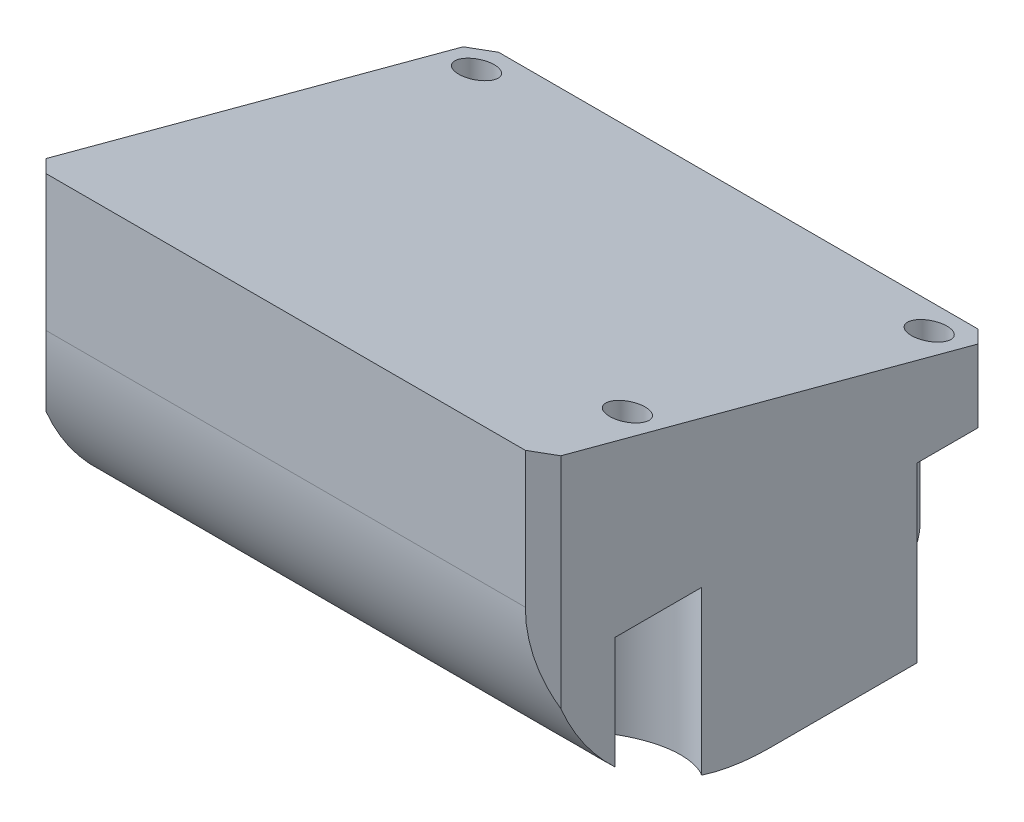
SolidWorks part; units mm, degrees
ref_plane "Front Plane" through (0, 0, 0) normal (0, 0, 1) x (1, 0, 0)
ref_plane "Top Plane" through (0, 0, 0) normal (0, 1, 0) x (1, 0, 0)
ref_plane "Right Plane" through (0, 0, 0) normal (1, 0, 0) x (0, 0, -1)
ref_plane "Plane1" through (-29, 0, 0) normal (-1, 0, 0) x (0, -1, 0)
sketch "Sketch1" plane through (-29, 0, 0) normal (-1, 0, 0) x (0, -1, 0)
  line L0 (125.5, 25.5) -> (84.6933, 25.5)
  line L1 (84.6933, 25.5) -> (98.3587, -25.5)
  line L2 (98.3587, -25.5) -> (125.5, -25.5)
  line L3 (125.5, -25.5) -> (125.5, 25.5)
extrude "Boss-Extrude1" add sketch "Sketch1" against normal blind 11
sketch "Sketch2" plane through (-18, 0, 0) normal (1, 0, 0) x (0, 0, -1)
  line L0 (25.5, -107.1795) -> (15.5, -104.5)
  line L1 (15.5, -104.5) -> (9.8731, -125.5)
  line L2 (9.8731, -125.5) -> (-25.5, -125.5)
  line L3 (-25.5, -125.5) -> (-25.5, -84.6933)
  line L4 (-25.5, -84.6933) -> (25.5, -98.3587)
  line L5 (25.5, -98.3587) -> (25.5, -107.1795)
extrude "Boss-Extrude2" add sketch "Sketch2" along normal blind 36
sketch "Sketch3" plane through (18, 0, 0) normal (1, 0, 0) x (0, 0, -1)
  line L0 (-25.5, -125.5) -> (-25.5, -84.6933)
  line L1 (-25.5, -84.6933) -> (25.5, -98.3587)
  line L2 (25.5, -98.3587) -> (25.5, -125.5)
  line L3 (25.5, -125.5) -> (-25.5, -125.5)
extrude "Boss-Extrude3" add sketch "Sketch3" along normal blind 11
sketch "Sketch4" plane through (0, -125.5, 0) normal (0, -1, 0) x (1, 0, 0)
  line L0 (29, -25.5) -> (29, -16.6266)
  line L1 (20.4786, -24.7841) -> (20.4786, -25.5)
  line L2 (20.4786, -25.5) -> (29, -25.5)
  arc A0 (29, -16.6266) -> (20.4786, -24.7841) centre (25.5, -21.5) ccw
extrude "Cut-Extrude1" cut sketch "Sketch4" against normal blind 19.5
sketch "Sketch5" plane through (0, -125.5, 0) normal (0, -1, 0) x (1, 0, 0)
  line L0 (-20.4786, -25.5) -> (-20.4786, -24.7841)
  line L1 (-29, -16.6266) -> (-29, -25.5)
  line L2 (-29, -25.5) -> (-20.4786, -25.5)
  arc A0 (-20.4786, -24.7841) -> (-29, -16.6266) centre (-25.5, -21.5) ccw
extrude "Cut-Extrude2" cut sketch "Sketch5" against normal blind 19.5
hole_wizard "Ø3.9 (3.9) Diameter Hole1" positions "Sketch7" profile "Sketch6" hole size "Ø3.9" standard "ANSI Metric"
sketch "Sketch7" plane through (0, -10.8752, -40.5867) normal (0, -0.2588, -0.9659) x (-1, 0, 0)
  point P0 (0, -111.9184)
  point P1 (-11, -111.9184)
  point P2 (-5.5, -104.4184)
  point P3 (5.5, -104.4184)
  point P4 (11, -111.9184)
sketch "Sketch6" plane through (0, -118.98, -11.6201) normal (1, 0, 0) x (0, 0.9659, -0.2588)
  line L0 (0, 0) -> (0, 31.1717)
  line L1 (0, 31.1717) -> (1.95, 30)
  line L2 (1.95, 30) -> (1.95, 0)
  line L5 (1.95, 0) -> (0, 0)
  line L10 (0, 31.1717) -> (-1.95, 30) construction
  line L11 (0, -6.35) -> (0, 107.95) construction
  dimension "Hole Dia." = 3.9
  dimension "Hole Depth" = 30
  dimension "Drill Angle" = 118
hole_wizard "CBORE for M3.5 Hex Head Machine Screw1" positions "Sketch9" profile "Sketch8" counterbore size "M3.5" standard "ANSI Metric"
sketch "Sketch9" plane through (0, -125.5, 0) normal (0, -1, 0) x (-1, 0, 0)
  point P0 (-25.5, -12.5)
sketch "Sketch8" plane through (25.5, -125.5, 12.5) normal (1, 0, 0) x (0, 0, -1)
  line L0 (0, 0) -> (0, 40.8067)
  line L1 (0, 40.8067) -> (2, 40.8067)
  line L3 (2, 40.8067) -> (2, 19.5)
  line L4 (2, 19.5) -> (6, 19.5)
  line L5 (6, 19.5) -> (6, 0)
  line L7 (6, 0) -> (0, 0)
  line L11 (0, -6.35) -> (0, 107.95) construction
  dimension "Thru Hole Dia." = 4
  dimension "Thru Hole Depth" = 40.8067
  dimension "C'Bore Dia." = 12
  dimension "C'Bore Depth" = 19.5
hole_wizard "Ø4.0 (4) Diameter Hole1" positions "Sketch11" profile "Sketch10" hole size "Ø4.0" standard "ANSI Metric"
sketch "Sketch11" plane through (0, -106, 0) normal (0, -1, 0) x (-1, 0, 0)
  point P0 (25.5, 21.5)
  point P1 (-25.5, 21.5)
sketch "Sketch10" plane through (-25.5, -106, -21.5) normal (1, 0, 0) x (0, 0, -1)
  line L0 (0, 0) -> (0, 21.3067)
  line L1 (0, 21.3067) -> (2, 21.3067)
  line L2 (2, 21.3067) -> (2, 0)
  line L5 (2, 0) -> (0, 0)
  line L11 (0, -6.35) -> (0, 107.95) construction
  dimension "Thru Hole Dia." = 4
  dimension "Thru Hole Depth" = 21.3067
chamfer "Chamfer1" distance 2 angle 45 5 edges at (-29, -102.1793, -25.5) (-29, -105.0966, 25.5) (-29, -125.5, 4.4367) (29, -105.0966, 25.5) (29, -102.1793, -25.5)
fillet "Fillet4" radius 5 2 edges at (19.2393, -125.5, -25.5) (-19.2393, -125.5, -25.5)
fillet "Fillet5" radius 6 2 edges at (18, -105.8397, -20.5) (-18, -105.8397, -20.5)
sketch "Sketch12" plane through (29, 0, 0) normal (1, 0, 0) x (0, 0, -1)
  line L0 (-25.5, -125.5) -> (-25.5, -84.6933) construction
  line L2 (-23.5, -125.5) -> (-17.3734, -125.5) construction
  line L3 (0, -125.5) -> (-25.5, -125.5)
  line L4 (-25.5, -125.5) -> (-25.5, -100)
  arc A0 (-25.5, -100) -> (0, -125.5) centre (0, -100) ccw
  dimension "D1" = 25.5
extrude "Cut-Extrude3" cut sketch "Sketch12" against normal through all
